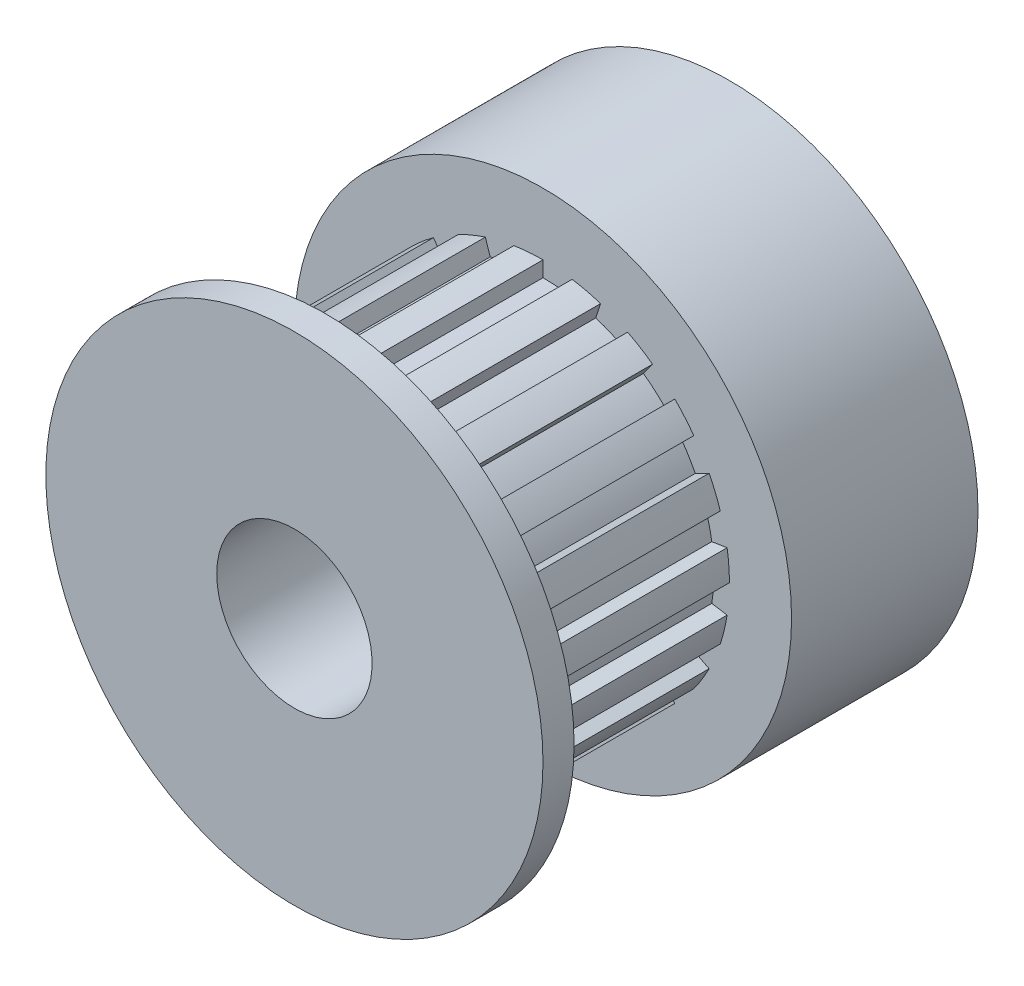
SolidWorks part; units mm, degrees
ref_plane "Front Plane" through (0, 0, 0) normal (0, 0, 1) x (1, 0, 0)
ref_plane "Top Plane" through (0, 0, 0) normal (0, 1, 0) x (1, 0, 0)
ref_plane "Right Plane" through (0, 0, 0) normal (1, 0, 0) x (0, 0, -1)
sketch "Sketch1" plane through (0, 0, 0) normal (0, 0, 1) x (1, 0, 0)
  circle A0 centre (0, 0) radius 8
  dimension "D1" = 16
extrude "Boss-Extrude1" add sketch "Sketch1" along normal blind 6
sketch "Sketch2" plane through (0, 0, 6) normal (0, 0, 1) x (1, 0, 0)
  line L0 (0, 5.5) -> (0, 6)
  line L1 (0.8604, 5.4323) -> (0.9386, 5.9261)
  line L2 (1.6996, 5.2308) -> (1.8541, 5.7063)
  line L3 (2.4969, 4.9005) -> (2.7239, 5.346)
  line L4 (3.2328, 4.4496) -> (3.5267, 4.8541)
  line L5 (3.8891, 3.8891) -> (4.2426, 4.2426)
  line L6 (4.4496, 3.2328) -> (4.8541, 3.5267)
  line L7 (4.9005, 2.4969) -> (5.346, 2.7239)
  line L8 (5.2308, 1.6996) -> (5.7063, 1.8541)
  line L9 (5.4323, 0.8604) -> (5.9261, 0.9386)
  line L10 (5.5, 0) -> (6, 0)
  line L11 (5.4323, -0.8604) -> (5.9261, -0.9386)
  line L12 (5.2308, -1.6996) -> (5.7063, -1.8541)
  line L13 (4.9005, -2.4969) -> (5.346, -2.7239)
  line L14 (4.4496, -3.2328) -> (4.8541, -3.5267)
  line L15 (3.8891, -3.8891) -> (4.2426, -4.2426)
  line L16 (3.2328, -4.4496) -> (3.5267, -4.8541)
  line L17 (2.4969, -4.9005) -> (2.7239, -5.346)
  line L18 (1.6996, -5.2308) -> (1.8541, -5.7063)
  line L19 (0.8604, -5.4323) -> (0.9386, -5.9261)
  line L20 (0, -5.5) -> (0, -6)
  line L21 (-0.8604, -5.4323) -> (-0.9386, -5.9261)
  line L22 (-1.6996, -5.2308) -> (-1.8541, -5.7063)
  line L23 (-2.4969, -4.9005) -> (-2.7239, -5.346)
  line L24 (-3.2328, -4.4496) -> (-3.5267, -4.8541)
  line L25 (-3.8891, -3.8891) -> (-4.2426, -4.2426)
  line L26 (-4.4496, -3.2328) -> (-4.8541, -3.5267)
  line L27 (-4.9005, -2.4969) -> (-5.346, -2.7239)
  line L28 (-5.2308, -1.6996) -> (-5.7063, -1.8541)
  line L29 (-5.4323, -0.8604) -> (-5.9261, -0.9386)
  line L30 (-5.5, 0) -> (-6, 0)
  line L31 (-5.4323, 0.8604) -> (-5.9261, 0.9386)
  line L32 (-5.2308, 1.6996) -> (-5.7063, 1.8541)
  line L33 (-4.9005, 2.4969) -> (-5.346, 2.7239)
  line L34 (-4.4496, 3.2328) -> (-4.8541, 3.5267)
  line L35 (-3.8891, 3.8891) -> (-4.2426, 4.2426)
  line L36 (-3.2328, 4.4496) -> (-3.5267, 4.8541)
  line L37 (-2.4969, 4.9005) -> (-2.7239, 5.346)
  line L38 (-1.6996, 5.2308) -> (-1.8541, 5.7063)
  line L39 (-0.8604, 5.4323) -> (-0.9386, 5.9261)
  arc A0 (0, 6) -> (-0.9386, 5.9261) centre (0, 0) ccw
  arc A1 (0.8604, 5.4323) -> (0, 5.5) centre (0, 0) ccw
  arc A2 (1.8541, 5.7063) -> (0.9386, 5.9261) centre (0, 0) ccw
  arc A3 (2.4969, 4.9005) -> (1.6996, 5.2308) centre (0, 0) ccw
  arc A4 (3.5267, 4.8541) -> (2.7239, 5.346) centre (0, 0) ccw
  arc A5 (3.8891, 3.8891) -> (3.2328, 4.4496) centre (0, 0) ccw
  arc A6 (4.8541, 3.5267) -> (4.2426, 4.2426) centre (0, 0) ccw
  arc A7 (4.9005, 2.4969) -> (4.4496, 3.2328) centre (0, 0) ccw
  arc A8 (5.7063, 1.8541) -> (5.346, 2.7239) centre (0, 0) ccw
  arc A9 (5.4323, 0.8604) -> (5.2308, 1.6996) centre (0, 0) ccw
  arc A10 (6, 0) -> (5.9261, 0.9386) centre (0, 0) ccw
  arc A11 (5.4323, -0.8604) -> (5.5, 0) centre (0, 0) ccw
  arc A12 (5.7063, -1.8541) -> (5.9261, -0.9386) centre (0, 0) ccw
  arc A13 (4.9005, -2.4969) -> (5.2308, -1.6996) centre (0, 0) ccw
  arc A14 (4.8541, -3.5267) -> (5.346, -2.7239) centre (0, 0) ccw
  arc A15 (3.8891, -3.8891) -> (4.4496, -3.2328) centre (0, 0) ccw
  arc A16 (3.5267, -4.8541) -> (4.2426, -4.2426) centre (0, 0) ccw
  arc A17 (2.4969, -4.9005) -> (3.2328, -4.4496) centre (0, 0) ccw
  arc A18 (1.8541, -5.7063) -> (2.7239, -5.346) centre (0, 0) ccw
  arc A19 (0.8604, -5.4323) -> (1.6996, -5.2308) centre (0, 0) ccw
  arc A20 (0, -6) -> (0.9386, -5.9261) centre (0, 0) ccw
  arc A21 (-0.8604, -5.4323) -> (0, -5.5) centre (0, 0) ccw
  arc A22 (-1.8541, -5.7063) -> (-0.9386, -5.9261) centre (0, 0) ccw
  arc A23 (-2.4969, -4.9005) -> (-1.6996, -5.2308) centre (0, 0) ccw
  arc A24 (-3.5267, -4.8541) -> (-2.7239, -5.346) centre (0, 0) ccw
  arc A25 (-3.8891, -3.8891) -> (-3.2328, -4.4496) centre (0, 0) ccw
  arc A26 (-4.8541, -3.5267) -> (-4.2426, -4.2426) centre (0, 0) ccw
  arc A27 (-4.9005, -2.4969) -> (-4.4496, -3.2328) centre (0, 0) ccw
  arc A28 (-5.7063, -1.8541) -> (-5.346, -2.7239) centre (0, 0) ccw
  arc A29 (-5.4323, -0.8604) -> (-5.2308, -1.6996) centre (0, 0) ccw
  arc A30 (-6, 0) -> (-5.9261, -0.9386) centre (0, 0) ccw
  arc A31 (-5.4323, 0.8604) -> (-5.5, 0) centre (0, 0) ccw
  arc A32 (-5.7063, 1.8541) -> (-5.9261, 0.9386) centre (0, 0) ccw
  arc A33 (-4.9005, 2.4969) -> (-5.2308, 1.6996) centre (0, 0) ccw
  arc A34 (-4.8541, 3.5267) -> (-5.346, 2.7239) centre (0, 0) ccw
  arc A35 (-3.8891, 3.8891) -> (-4.4496, 3.2328) centre (0, 0) ccw
  arc A36 (-3.5267, 4.8541) -> (-4.2426, 4.2426) centre (0, 0) ccw
  arc A37 (-2.4969, 4.9005) -> (-3.2328, 4.4496) centre (0, 0) ccw
  arc A38 (-1.8541, 5.7063) -> (-2.7239, 5.346) centre (0, 0) ccw
  arc A39 (-0.8604, 5.4323) -> (-1.6996, 5.2308) centre (0, 0) ccw
  point P86 (0, 0)
  dimension "D1" = 12
  dimension "D2" = 11
  dimension "D3" = 40
extrude "Boss-Extrude2" add sketch "Sketch2" along normal blind 7
sketch "Sketch3" plane through (0, 0, 13) normal (0, 0, 1) x (1, 0, 0)
  circle A0 centre (0, 0) radius 8
  dimension "D1" = 16
extrude "Boss-Extrude3" add sketch "Sketch3" along normal blind 1
sketch "Sketch4" plane through (0, 0, 0) normal (0, 0, -1) x (-1, 0, 0)
  circle A0 centre (0, 0) radius 2.5
  dimension "D1" = 5
extrude "Cut-Extrude1" cut sketch "Sketch4" against normal through all
sketch "Sketch5" plane through (0, 0, 0) normal (0, 1, 0) x (1, 0, 0)
  circle A0 centre (0, -3) radius 1.7
  dimension "D1" = 3.4
  dimension "D2" = 3
extrude "Cut-Extrude2" cut sketch "Sketch5" against normal through all
